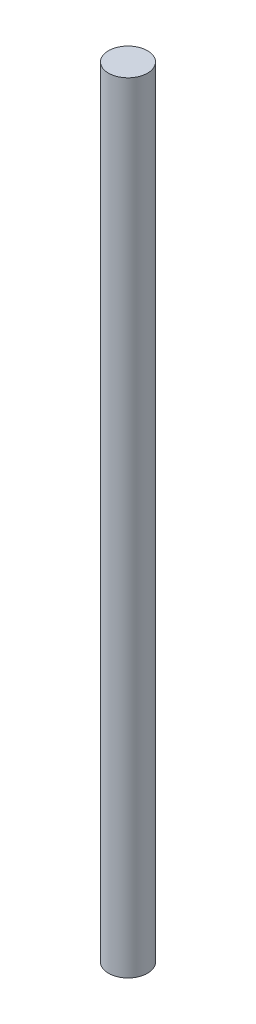
SolidWorks part; units mm, degrees
ref_plane "Front Plane" through (0, 0, 0) normal (0, 0, 1) x (1, 0, 0)
ref_plane "Top Plane" through (0, 0, 0) normal (0, 1, 0) x (1, 0, 0)
ref_plane "Right Plane" through (0, 0, 0) normal (1, 0, 0) x (0, 0, -1)
sketch "Sketch1" plane through (0, 0, 0) normal (0, 1, 0) x (1, 0, 0)
  circle A0 centre (0, 0) radius 2
  dimension "D1" = 4
extrude "Boss-Extrude1" add sketch "Sketch1" along normal blind 80
